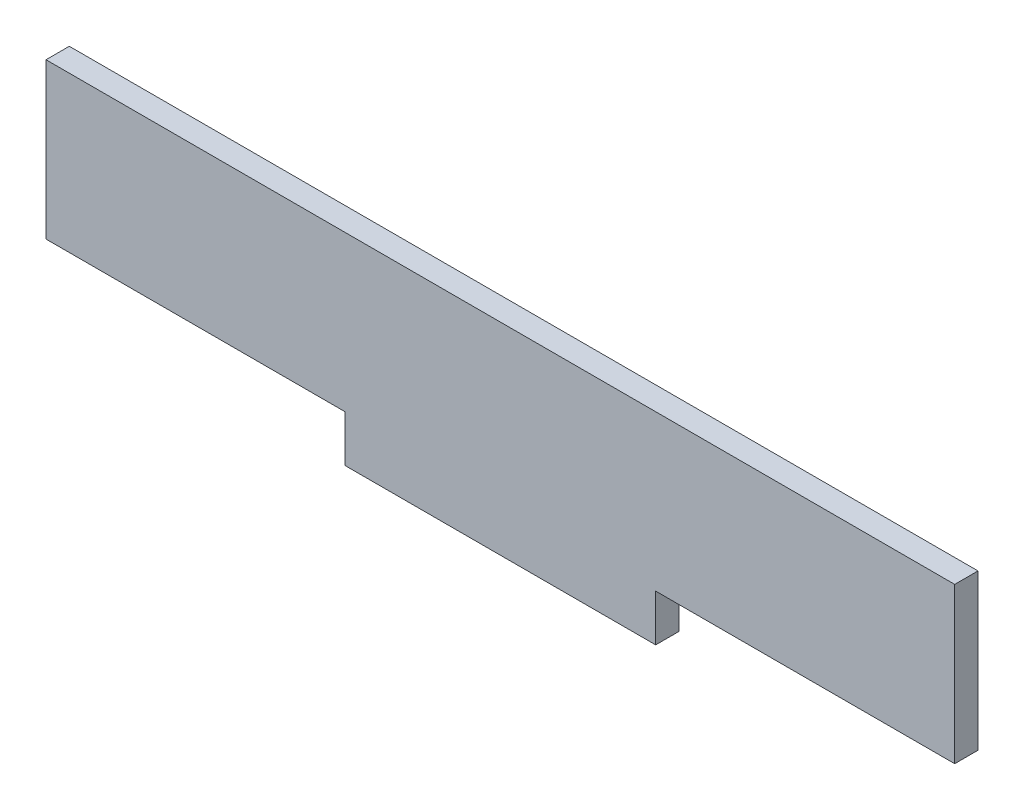
SolidWorks part; units mm, degrees
material "Acrylic (Medium-high impact)"
ref_plane "Alzado" through (0, 0, 0) normal (0, 0, 1) x (1, 0, 0)
ref_plane "Planta" through (0, 0, 0) normal (0, 1, 0) x (1, 0, 0)
ref_plane "Vista lateral" through (0, 0, 0) normal (1, 0, 0) x (0, 0, -1)
sketch "Sketch1" plane through (0, 0, 0) normal (0, 0, 1) x (1, 0, 0)
  line L0 (0, 0) -> (38.5, 0)
  line L1 (38.5, 0) -> (38.5, -6)
  line L2 (38.5, -6) -> (78.5, -6)
  line L3 (78.5, -6) -> (78.5, 0)
  line L4 (78.5, 0) -> (117, 0)
  line L5 (117, 0) -> (117, 20)
  line L6 (117, 20) -> (0, 20)
  line L7 (0, 20) -> (0, 0)
  dimension "D1" = 117
  dimension "D2" = 40
  dimension "D3" = 6
  dimension "D4" = 26
extrude "Boss-Extrude1" add sketch "Sketch1" along normal blind 3
